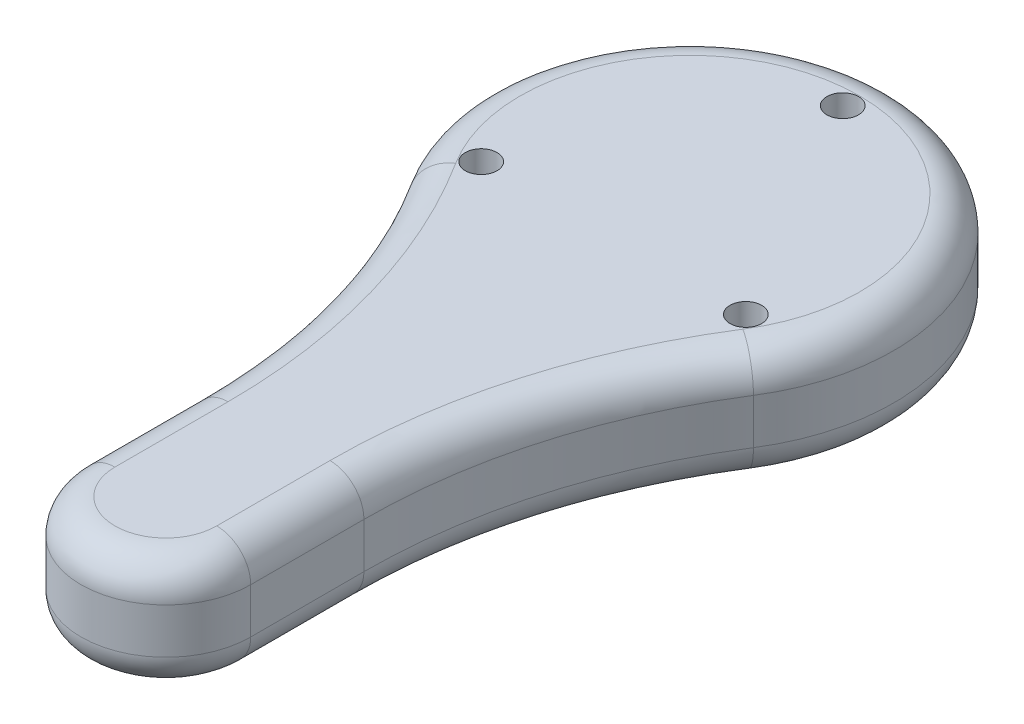
SolidWorks part; units mm, degrees
ref_plane "Front Plane" through (0, 0, 0) normal (0, 0, 1) x (1, 0, 0)
ref_plane "Top Plane" through (0, 0, 0) normal (0, 1, 0) x (1, 0, 0)
ref_plane "Right Plane" through (0, 0, 0) normal (1, 0, 0) x (0, 0, -1)
sketch "Sketch1" plane through (0, 0, 0) normal (0, 1, 0) x (1, 0, 0)
  line L0 (0, 0) -> (0, -46.3008) construction
  line L1 (7.5, -36.3008) -> (7.5, -46.3008)
  line L2 (-7.5, -36.3008) -> (-7.5, -46.3008)
  arc A0 (15.2206, -9.609) -> (-15.2206, -9.609) centre (0, 0) ccw
  arc A2 (-7.5, -46.3008) -> (7.5, -46.3008) centre (0, -46.3008) ccw
  arc A3 (15.2206, -9.609) -> (7.5, -36.3008) centre (57.5, -36.3008) ccw
  arc A4 (-7.5, -36.3008) -> (-15.2206, -9.609) centre (-57.5, -36.3008) ccw
  dimension "D1" = 36
  dimension "D2" = 50
  dimension "D3" = 10
  dimension "D4" = 15
extrude "Boss-Extrude1" add sketch "Sketch1" along normal blind 10
fillet "Fillet1" radius 3 12 edges at (0, 0, -18) (-9.4689, 0, 22.4079) (-7.5, 0, 41.3008) (0, 0, 53.8008) (7.5, 0, 41.3008) (9.4689, 0, 22.4079) (7.5, 10, 41.3008) (0, 10, 53.8008) (-7.5, 10, 41.3008) (-9.4689, 10, 22.4079) (0, 10, -18) (9.4689, 10, 22.4079)
sketch "Sketch2" plane through (0, 10, 0) normal (0, 1, 0) x (1, 0, 0)
  arc A0 (-11.6913, -7.775) -> (-11.6913, -5.725) centre (-11.6913, -6.75) ccw construction
  arc A1 (11.6913, -7.775) -> (11.6913, -5.725) centre (11.6913, -6.75) ccw construction
  arc A2 (0, 12.475) -> (0, 14.525) centre (0, 13.5) ccw construction
  arc A3 (-11.6913, -7.775) -> (-11.6913, -5.725) centre (-11.6913, -6.75) ccw construction
  arc A4 (11.6913, -7.775) -> (11.6913, -5.725) centre (11.6913, -6.75) ccw construction
  arc A5 (0, 12.475) -> (0, 14.525) centre (0, 13.5) ccw construction
  circle A6 centre (0, 13.5) radius 1.4
  circle A7 centre (-11.6913, -6.75) radius 1.4
  circle A8 centre (11.6913, -6.75) radius 1.4
  dimension "D1" = 2.8
extrude "Cut-Extrude1" cut sketch "Sketch2" against normal through all
